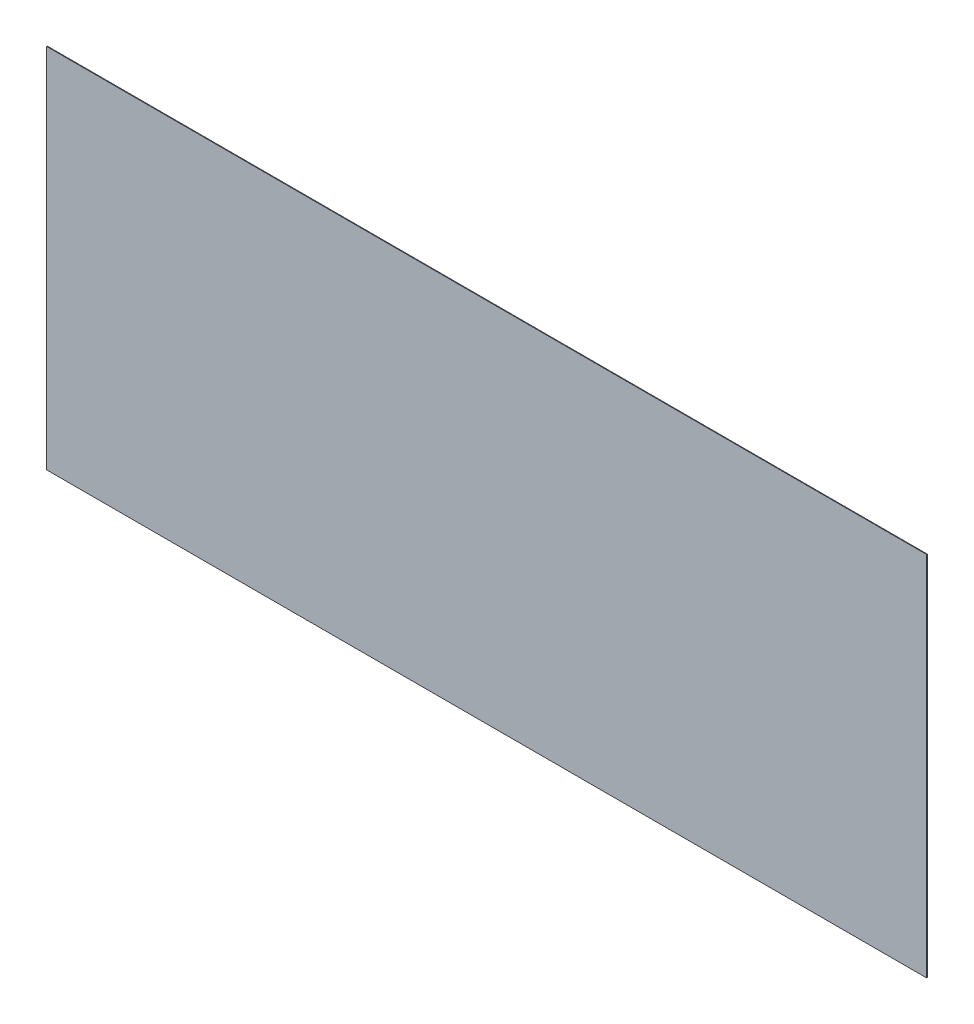
SolidWorks part; units mm, degrees
ref_plane "Alzado" through (0, 0, 0) normal (0, 0, 1) x (1, 0, 0)
ref_plane "Planta" through (0, 0, 0) normal (0, 1, 0) x (1, 0, 0)
ref_plane "Vista lateral" through (0, 0, 0) normal (1, 0, 0) x (0, 0, -1)
sketch "Croquis1" plane through (0, 0, 0) normal (0, 0, 1) x (1, 0, 0)
  line L1 (-381.5135, 331.3808) -> (818.4865, 331.3808)
  line L2 (-381.5135, 331.3808) -> (-381.5135, -168.6192)
  line L3 (-381.5135, -168.6192) -> (818.4865, -168.6192)
  line L4 (818.4865, 331.3808) -> (818.4865, -168.6192)
  dimension "D1" = 1200
  dimension "D2" = 500
extrude "Saliente-Extruir1" add sketch "Croquis1" along normal blind 0.9
